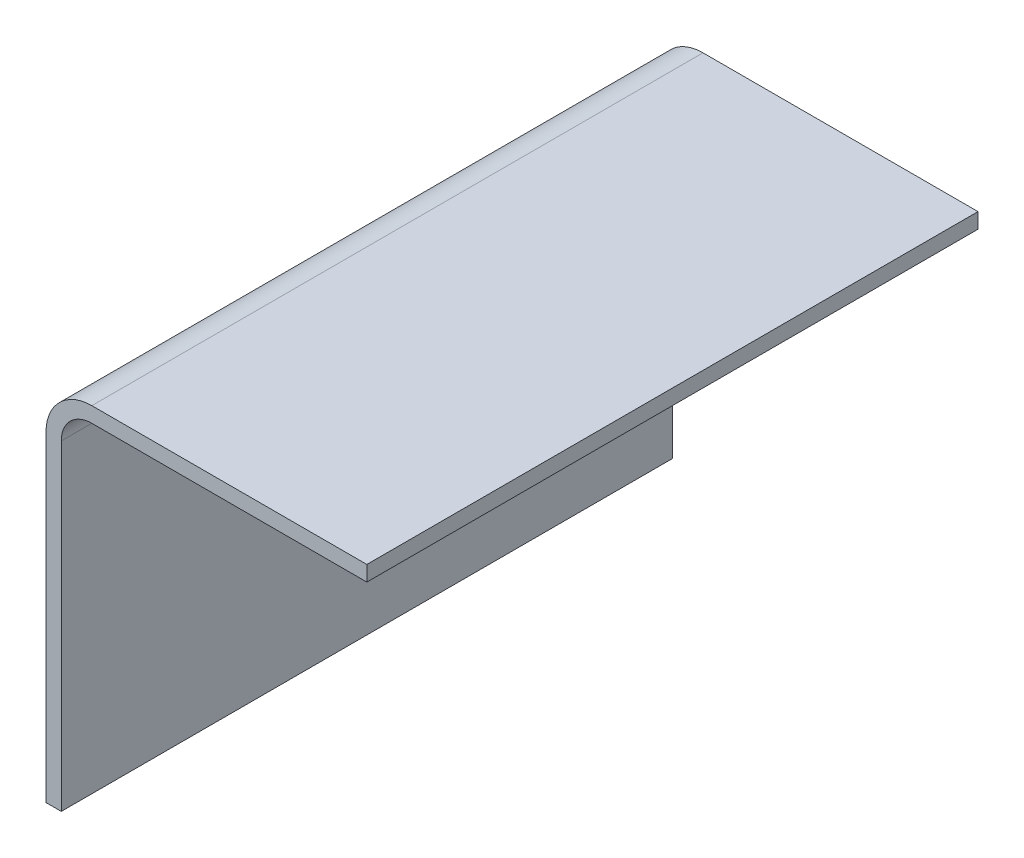
SolidWorks part; units mm, degrees
ref_plane "前视基准面" through (0, 0, 0) normal (0, 0, 1) x (1, 0, 0)
ref_plane "上视基准面" through (0, 0, 0) normal (0, 1, 0) x (1, 0, 0)
ref_plane "右视基准面" through (0, 0, 0) normal (1, 0, 0) x (0, 0, -1)
other "Configuration Table"
sketch "草图2" plane through (0, 0, 0) normal (0, 0, 1) x (1, 0, 0)
  line L1 (0, 10) -> (0, 115)
  line L2 (10, 125) -> (90, 125)
  line L40 (100, 130) -> (100, 125)
  line L44 (90, 125) -> (100, 125)
  line L45 (-5, 10) -> (0, 10)
  line L48 (-5, 20) -> (-5, 10)
  line L49 (100, 130) -> (10, 130)
  line L50 (-5, 115) -> (-5, 20)
  arc A0 (10, 125) -> (0, 115) centre (10, 115) ccw
  arc A1 (10, 130) -> (-5, 115) centre (10, 115) ccw
  dimension "D1" = 10
  dimension "D2" = 15
  dimension "D4" = 10
  dimension "D5" = 10
extrude "凸台-拉伸1" add sketch "草图2" along normal blind 200
